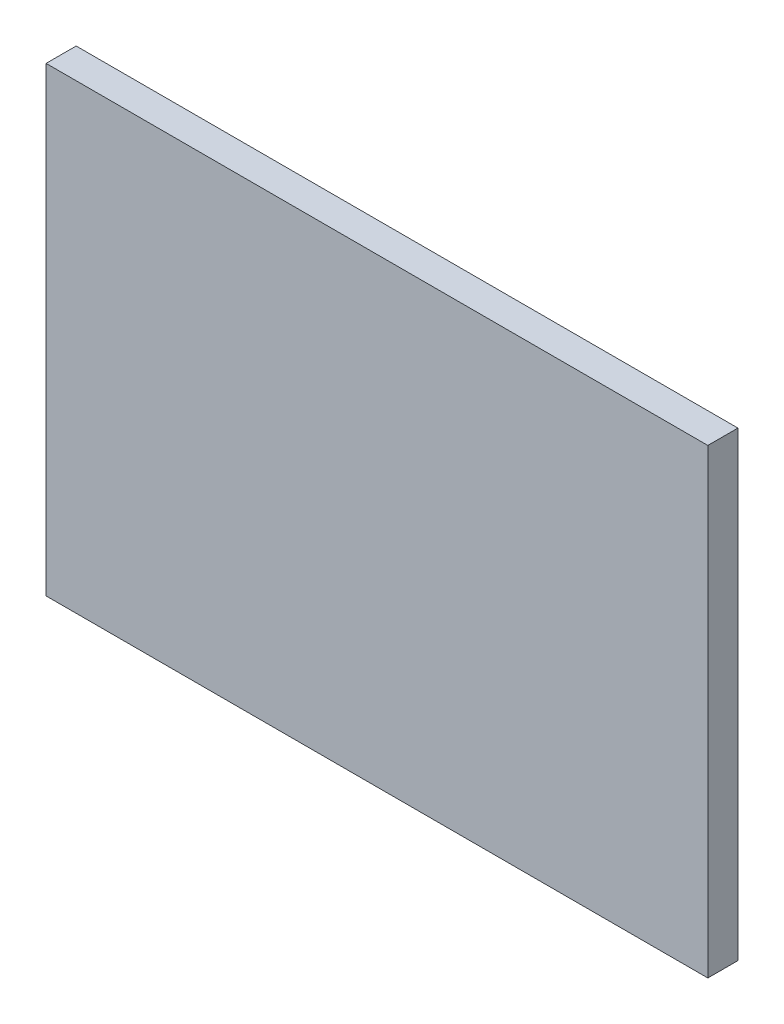
SolidWorks part; units mm, degrees
ref_plane "Front Plane" through (0, 0, 0) normal (0, 0, 1) x (1, 0, 0)
ref_plane "Top Plane" through (0, 0, 0) normal (0, 1, 0) x (1, 0, 0)
ref_plane "Right Plane" through (0, 0, 0) normal (1, 0, 0) x (0, 0, -1)
sketch "Sketch1" plane through (0, 0, 0) normal (0, 0, 1) x (1, 0, 0)
  line L1 (-33, 23) -> (33, 23)
  line L2 (-33, 23) -> (-33, -23)
  line L3 (-33, -23) -> (33, -23)
  line L4 (33, 23) -> (33, -23)
  line L5 (-33, 23) -> (33, -23) construction
  line L6 (-33, -23) -> (33, 23) construction
  point P0 (0, 0)
  dimension "D1" = 46
  dimension "D2" = 66
extrude "Boss-Extrude1" add sketch "Sketch1" along normal blind 3
